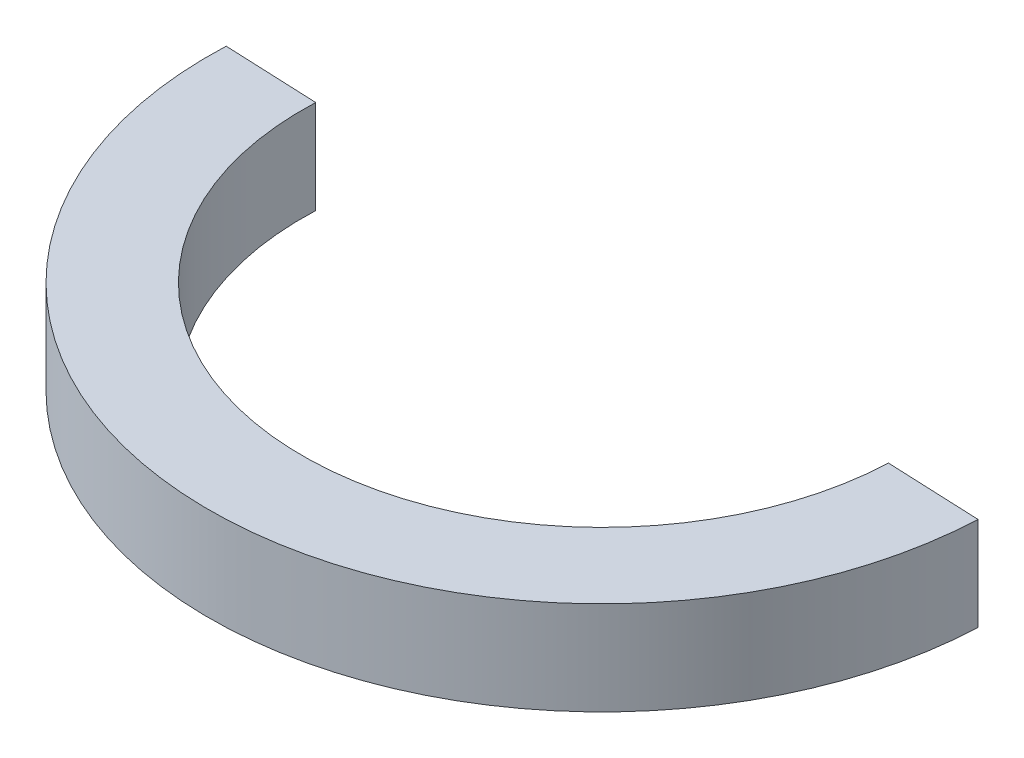
SolidWorks part; units mm, degrees
ref_plane "Спереди" through (0, 0, 0) normal (0, 0, 1) x (1, 0, 0)
ref_plane "Сверху" through (0, 0, 0) normal (0, 1, 0) x (1, 0, 0)
ref_plane "Справа" through (0, 0, 0) normal (1, 0, 0) x (0, 0, -1)
other "Configuration Table"
sketch "Эскиз2" plane through (0, 0, 0) normal (0, 1, 0) x (1, 0, 0)
  arc A0 (-31.9702, 1.3814) -> (31.9702, -1.3814) centre (0, 0) ccw
extrude "Вытянуть-Тонкостенный1" add sketch "Эскиз2" along normal blind 10 thin
